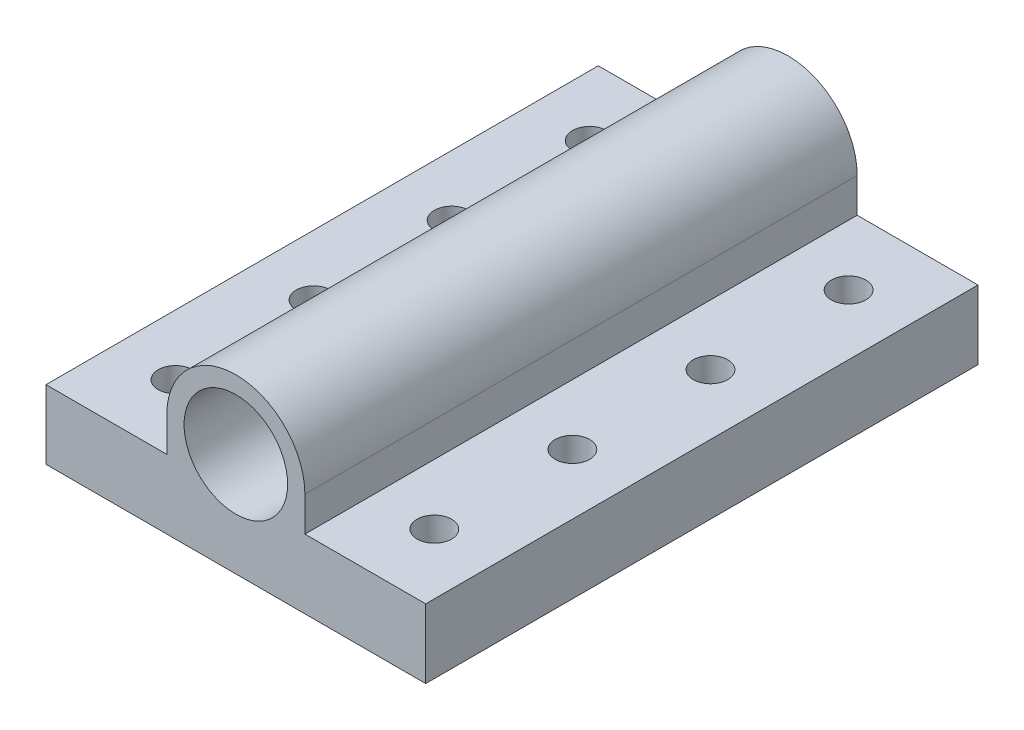
SolidWorks part; units mm, degrees
ref_plane "Front Plane" through (0, 0, 0) normal (0, 0, 1) x (1, 0, 0)
ref_plane "Top Plane" through (0, 0, 0) normal (0, 1, 0) x (1, 0, 0)
ref_plane "Right Plane" through (0, 0, 0) normal (1, 0, 0) x (0, 0, -1)
sketch "Sketch1" plane through (0, 0, 0) normal (0, 0, 1) x (1, 0, 0)
  line L1 (0, 0) -> (-17.5, 0)
  line L2 (0, 0) -> (0, -10)
  line L3 (0, -10) -> (-55, -10)
  line L4 (-55, 0) -> (-55, -10)
  line L5 (-17.5, 0) -> (-17.5, 5)
  line L6 (-37.5, 0) -> (-37.5, 5)
  line L7 (-55, 0) -> (-55, 1.544) construction
  line L8 (-37.5, 0) -> (-55, 0)
  arc A0 (-37.5, 5) -> (-17.5, 5) centre (-27.5, 5) cw
  circle A1 centre (-27.5, 5) radius 7.5
  dimension "D4" = 10
  dimension "D6" = 15
  dimension "D1" = 55
  dimension "D2" = 10
  dimension "D3" = 5
  dimension "D5" = 27.5
extrude "Boss-Extrude2" add sketch "Sketch1" along normal blind 80
sketch "Sketch3" plane through (0, 0, 0) normal (0, 1, 0) x (1, 0, 0)
  line L0 (0, 0) -> (-55, 0) construction
  line L1 (-27.5, 0) -> (-27.5, -80) construction
  line L2 (-37.5, -80) -> (-17.5, -80) construction
  line L3 (0, -80) -> (-17.5, -80) construction
  line L6 (-8.75, 30.7874) -> (-8.75, -83.5203) construction
  circle A0 centre (-8.75, -10) radius 2.5
  circle A1 centre (-8.75, -30) radius 2.5
  circle A2 centre (-8.75, -50) radius 2.5
  circle A3 centre (-8.75, -70) radius 2.5
  circle A4 centre (-46.25, -70) radius 2.5
  circle A5 centre (-46.25, -50) radius 2.5
  circle A6 centre (-46.25, -30) radius 2.5
  circle A7 centre (-46.25, -10) radius 2.5
  point P17 (-8.75, -26.3664)
  dimension "D4" = 5
  dimension "D5" = 5
  dimension "D6" = 5
  dimension "D7" = 5
  dimension "D1" = 10
  dimension "D2" = 10
  dimension "2" = 30
  dimension "D3" = 30
extrude "Cut-Extrude1" cut sketch "Sketch3" against normal blind 2000
